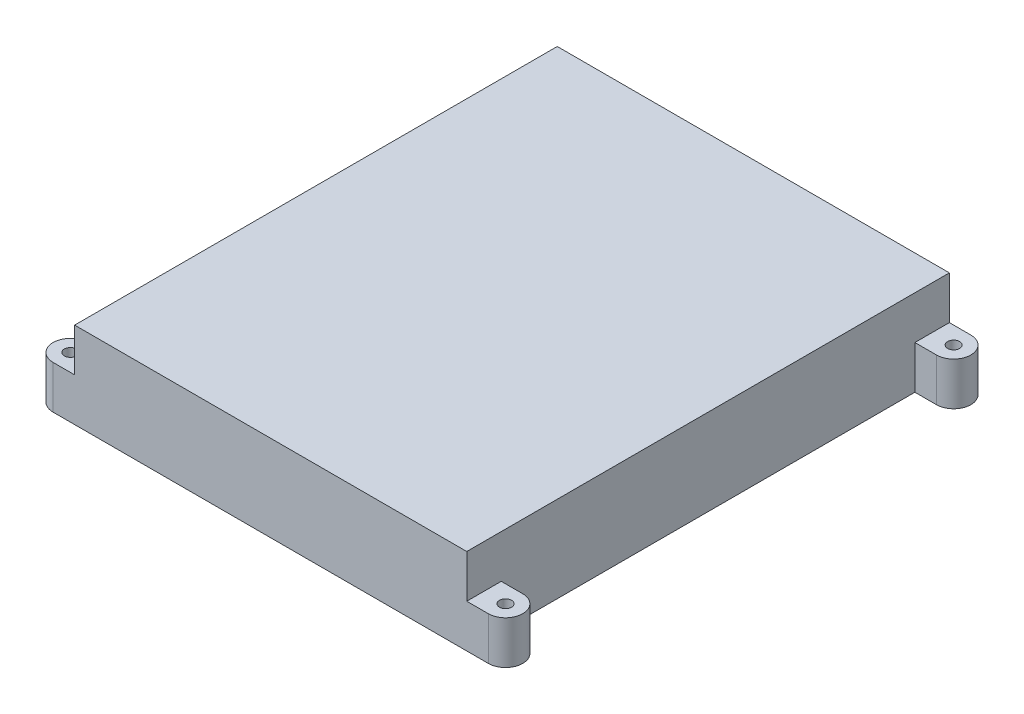
SolidWorks part; units mm, degrees
ref_plane "Front Plane" through (0, 0, 0) normal (0, 0, 1) x (1, 0, 0)
ref_plane "Top Plane" through (0, 0, 0) normal (0, 1, 0) x (1, 0, 0)
ref_plane "Right Plane" through (0, 0, 0) normal (1, 0, 0) x (0, 0, -1)
sketch "Sketch1" plane through (0, 0, 0) normal (0, 1, 0) x (1, 0, 0)
  line L0 (0, 56) -> (0, -56) construction
  line L1 (-39.5, 50) -> (39.5, 50) construction
  line L2 (-39.5, 50) -> (-39.5, -50) construction
  line L3 (-39.5, -50) -> (39.5, -50) construction
  line L4 (39.5, 50) -> (39.5, -50) construction
  line L5 (-45.5, 56) -> (45.5, 56)
  line L6 (-45.5, 56) -> (-45.5, -56)
  line L7 (-45.5, -56) -> (45.5, -56)
  line L8 (45.5, 56) -> (45.5, -56)
  point P4 (-39.5, 0)
  point P6 (0, 50)
  dimension "D1" = 100
  dimension "D2" = 79
  dimension "D3" = 112
  dimension "D4" = 91
extrude "Base" add sketch "Sketch1" along normal blind 20
sketch "Sketch2" plane through (0, 0, 0) normal (0, 1, 0) x (1, 0, 0)
  line L0 (-45.5, 56) -> (-50.5, 56)
  line L1 (-45.5, 56) -> (-45.5, 48)
  line L2 (-45.5, 56) -> (-45.5, -56) construction
  line L3 (-45.5, 48) -> (-50.5, 48)
  line L6 (0, 56) -> (0, -56) construction
  line L7 (45.5, 56) -> (-45.5, 56) construction
  line L8 (-45.5, -56) -> (45.5, -56) construction
  line L9 (-45.5, 0) -> (45.5, 0) construction
  line L10 (45.5, -56) -> (45.5, 56) construction
  line L11 (45.5, 48) -> (50.5, 48)
  line L12 (45.5, 56) -> (45.5, 48)
  line L13 (45.5, 56) -> (50.5, 56)
  line L14 (45.5, -56) -> (50.5, -56)
  line L15 (45.5, -56) -> (45.5, -48)
  line L16 (45.5, -48) -> (50.5, -48)
  line L17 (-45.5, -48) -> (-50.5, -48)
  line L18 (-45.5, -56) -> (-45.5, -48)
  line L19 (-45.5, -56) -> (-50.5, -56)
  arc A0 (-50.5, 48) -> (-50.5, 56) centre (-50.5, 52) cw
  circle A1 centre (-50.5, 52) radius 1.4
  circle A2 centre (50.5, 52) radius 1.4
  arc A3 (50.5, 48) -> (50.5, 56) centre (50.5, 52) ccw
  arc A4 (50.5, -48) -> (50.5, -56) centre (50.5, -52) cw
  circle A5 centre (50.5, -52) radius 1.4
  circle A6 centre (-50.5, -52) radius 1.4
  arc A7 (-50.5, -48) -> (-50.5, -56) centre (-50.5, -52) ccw
  dimension "D2" = 2.8
  dimension "D1" = 8
  dimension "D3" = 5
extrude "Case Assembly Holes" add sketch "Sketch2" along normal blind 10
sketch "Sketch3" plane through (0, 0, 0) normal (0, -1, 0) x (1, 0, 0)
  line L1 (41.5, -52) -> (-41.5, -52)
  line L2 (41.5, -52) -> (41.5, 52)
  line L3 (41.5, 52) -> (-41.5, 52)
  line L4 (-41.5, -52) -> (-41.5, 52)
  line L5 (41.5, -52) -> (-41.5, 52) construction
  line L6 (41.5, 52) -> (-41.5, -52) construction
  point P0 (0, 0)
  dimension "D1" = 83
  dimension "D2" = 104
extrude "Module Cutout" cut sketch "Sketch3" against normal blind 6.6
sketch "Sketch4" plane through (-45.5, 0, 0) normal (-1, 0, 0) x (0, 0, 1)
  line L0 (-50, 0) -> (50, 0) construction
  line L1 (-48, 0) -> (48, 0) construction
  line L3 (-49.25, 0) -> (-38.75, 0)
  line L4 (-49.25, 0) -> (-49.25, 6)
  line L5 (-49.25, 6) -> (-38.75, 6)
  line L6 (-38.75, 0) -> (-38.75, 6)
  line L7 (47, 0) -> (37, 0)
  line L8 (47, 0) -> (47, 6)
  line L9 (47, 6) -> (37, 6)
  line L10 (37, 0) -> (37, 6)
  dimension "D1" = 100
  dimension "D2" = 6
  dimension "D3" = 10.5
  dimension "D4" = 0.75
  dimension "D5" = 10
  dimension "D6" = 3
extrude "USB-C and Micro-USB Slots" cut sketch "Sketch4" against normal blind 7 and the other way through all
sketch "Sketch5" plane through (-45.5, 0, 0) normal (-1, 0, 0) x (0, 0, 1)
  line L0 (-38.75, 0) -> (37, 0) construction
  line L1 (-34.5, 0) -> (-18, 0)
  line L2 (-34.5, 0) -> (-34.5, 10)
  line L3 (-34.5, 10) -> (-18, 10)
  line L4 (-18, 0) -> (-18, 10)
  line L5 (-50, 0) -> (50, 0) construction
  line L6 (1.1, 20) -> (1.1, 0) construction
  line L7 (-15.4, 0) -> (0.6, 0)
  line L8 (-15.4, 0) -> (-15.4, 19)
  line L9 (-15.4, 19) -> (0.6, 19)
  line L10 (0.6, 0) -> (0.6, 19)
  line L11 (-56, 20) -> (56, 20) construction
  line L12 (17.6, 19) -> (1.6, 19)
  line L13 (1.6, 0) -> (1.6, 19)
  line L14 (17.6, 0) -> (1.6, 0)
  line L15 (17.6, 0) -> (17.6, 19)
  point P10 (0, 0)
  point P21 (-7.4, 0)
  dimension "D1" = 100
  dimension "D2" = 15.5
  dimension "D3" = 16.5
  dimension "D4" = 10
  dimension "D5" = 34.6
  dimension "D6" = 16
  dimension "D7" = 19
  dimension "D8" = 8.5
extrude "HDMI and USB Slots" cut sketch "Sketch5" against normal blind 17.5
sketch "Sketch6" plane through (-45.5, 0, 0) normal (-1, 0, 0) x (0, 0, 1)
  line L0 (-50, 0) -> (50, 0) construction
  line L1 (-52, 0) -> (52, 0) construction
  line L3 (35.5, 0) -> (17.6, 0)
  line L4 (35.5, 0) -> (35.5, 16.2)
  line L5 (35.5, 16.2) -> (17.6, 16.2)
  line L6 (17.6, 0) -> (17.6, 16.2)
  line L7 (17.6, 0) -> (17.6, 19) construction
  point P4 (0, 0)
  dimension "D1" = 100
  dimension "D3" = 16.2
  dimension "D4" = 14.5
extrude "Ethernet Slot" cut sketch "Sketch6" against normal blind 21
sketch "Sketch7" plane through (0, 6.6, 0) normal (0, -1, 0) x (1, 0, 0)
  line L1 (-39.5, 50) -> (39.5, 50) construction
  line L2 (-39.5, 50) -> (-39.5, -50) construction
  line L3 (-39.5, -50) -> (39.5, -50) construction
  line L4 (39.5, 50) -> (39.5, -50) construction
  line L5 (-5.5, -43.75) -> (18.5, -43.75)
  line L6 (-5.5, -43.75) -> (-5.5, -48.75)
  line L7 (-5.5, -48.75) -> (18.5, -48.75)
  line L8 (18.5, -43.75) -> (18.5, -48.75)
  circle A0 centre (-20.05, -12.75) radius 3.6
  circle A1 centre (-15.25, 32.09) radius 3.6
  point P6 (0, -50)
  point P8 (-39.5, 0)
  dimension "D1" = 7.2
  dimension "D4" = 19.45
  dimension "D5" = 37.25
  dimension "D6" = 24.25
  dimension "D7" = 17.91
  dimension "D2" = 79
  dimension "D3" = 100
  dimension "D8" = 24
  dimension "D9" = 5
  dimension "D10" = 1.25
  dimension "D11" = 21
extrude "Tall Components Cutouts" cut sketch "Sketch7" against normal blind 3
